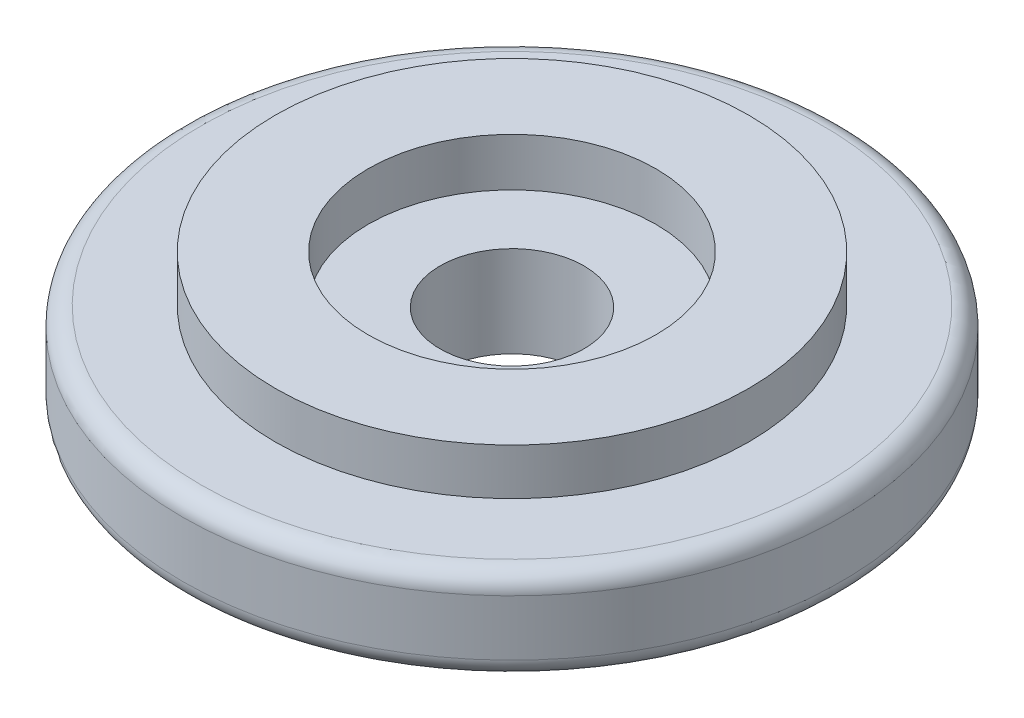
SolidWorks part; units mm, degrees
ref_plane "Front Plane" through (0, 0, 0) normal (0, 0, 1) x (1, 0, 0)
ref_plane "Top Plane" through (0, 0, 0) normal (0, 1, 0) x (1, 0, 0)
ref_plane "Right Plane" through (0, 0, 0) normal (1, 0, 0) x (0, 0, -1)
sketch "Sketch1" plane through (0, 0, 0) normal (0, 0, 1) x (1, 0, 0)
  line L0 (0, 0) -> (0, 7.1801) construction
  line L1 (1.55, 0.2026) -> (7.1, 0.2026)
  line L2 (7.1, 0.2026) -> (7.1, 2.2026)
  line L3 (7.1, 2.2026) -> (5.1, 2.2026)
  line L4 (5.1, 2.2026) -> (5.1, 3.2026)
  line L5 (5.1, 3.2026) -> (3.1, 3.2026)
  line L6 (3.1, 3.2026) -> (3.1, 2.1654)
  line L7 (3.1, 2.1654) -> (1.55, 2.1654)
  line L8 (1.55, 2.1654) -> (1.55, 0.2026)
  point P2 (0, 0)
  dimension "D1" = 1.55
  dimension "D2" = 2
  dimension "D3" = 3.1
  dimension "D4" = 2
  dimension "D5" = 2
  dimension "D6" = 1
revolve "Revolve1" add sketch "Sketch1" angle 360 about L0
fillet "Fillet1" radius 0.4 2 edges at (0, 0.2026, -7.1) (0, 2.2026, -7.1)
